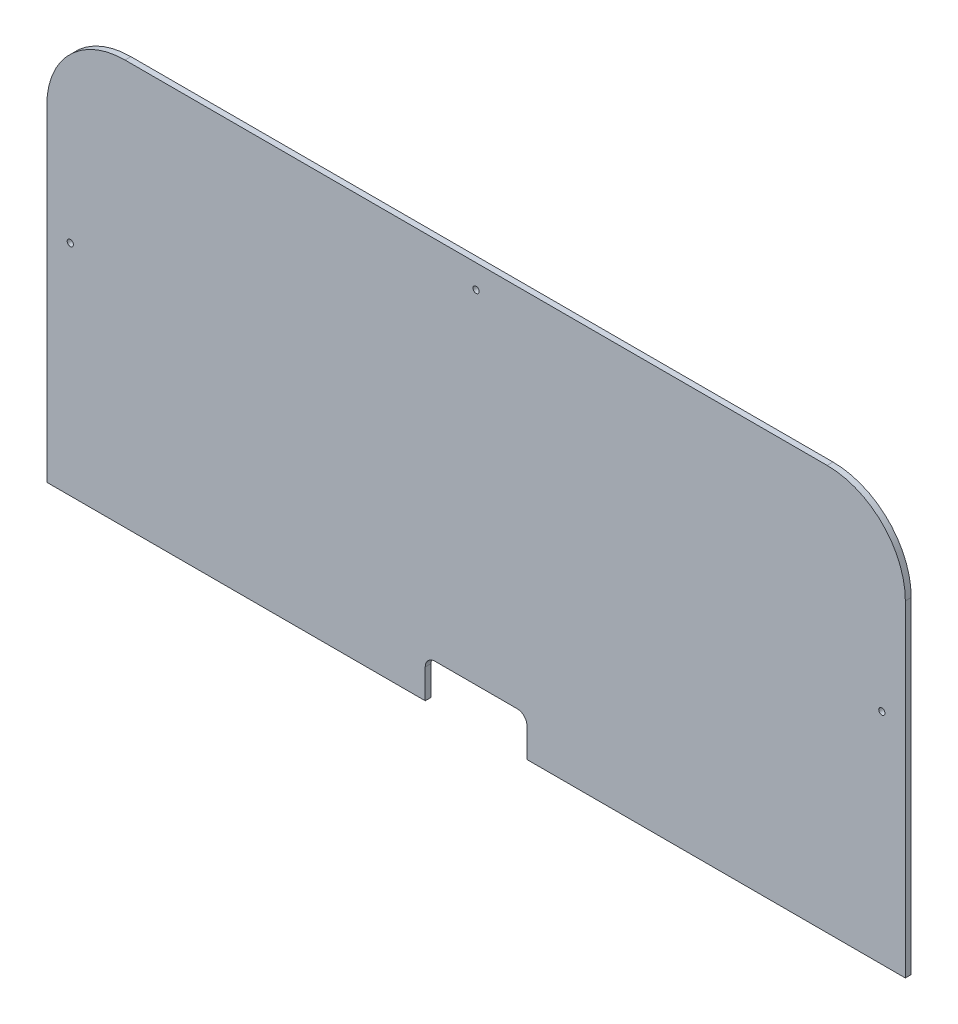
SolidWorks part; units mm, degrees
ref_plane "Front Plane" through (0, 0, 0) normal (0, 0, 1) x (1, 0, 0)
ref_plane "Top Plane" through (0, 0, 0) normal (0, 1, 0) x (1, 0, 0)
ref_plane "Right Plane" through (0, 0, 0) normal (1, 0, 0) x (0, 0, -1)
sketch "Sketch1" plane through (0, 0, 0) normal (0, 0, 1) x (1, 0, 0)
  line L1 (-219.5, 103.5) -> (219.5, 103.5)
  line L2 (-219.5, 103.5) -> (-219.5, -103.5)
  line L3 (-219.5, -103.5) -> (219.5, -103.5)
  line L4 (219.5, 103.5) -> (219.5, -103.5)
  line L5 (-219.5, 103.5) -> (219.5, -103.5) construction
  line L6 (-219.5, -103.5) -> (219.5, 103.5) construction
  point P0 (0, 0)
  dimension "D1" = 439
  dimension "D2" = 207
extrude "Boss-Extrude1" add sketch "Sketch1" along normal blind 3
fillet "Fillet1" radius 40 2 edges at (-219.5, 103.5, 1.5) (219.5, 103.5, 1.5)
sketch "Sketch2" plane through (0, 0, 0) normal (0, 0, -1) x (-1, 0, 0)
  line L0 (219.5, -103.5) -> (-219.5, -103.5) construction
  line L1 (-21, -83.5) -> (21, -83.5)
  line L2 (-26, -88.5) -> (-26, -103.5)
  line L3 (-26, -103.5) -> (26, -103.5)
  line L4 (26, -88.5) -> (26, -103.5)
  arc A0 (-21, -83.5) -> (-26, -88.5) centre (-21, -88.5) ccw
  arc A1 (21, -83.5) -> (26, -88.5) centre (21, -88.5) cw
  point P4 (0, -83.5)
  point P10 (-26, -83.5)
  point P13 (26, -83.5)
  dimension "D3" = 5
  dimension "D1" = 20
  dimension "D2" = 52
extrude "Cut-Extrude1" cut sketch "Sketch2" against normal through all
sketch "Sketch3" plane through (0, 0, 3) normal (0, 0, 1) x (1, 0, 0)
  circle A0 centre (-207.5, 8.5) radius 1.6
  circle A1 centre (207.5, 8.5) radius 1.6
extrude "Cut-Extrude2" cut sketch "Sketch3" against normal through all
sketch "Sketch4" plane through (0, 0, 3) normal (0, 0, 1) x (1, 0, 0)
  circle A0 centre (0, 91.5) radius 1.6
extrude "Cut-Extrude3" cut sketch "Sketch4" against normal through all
